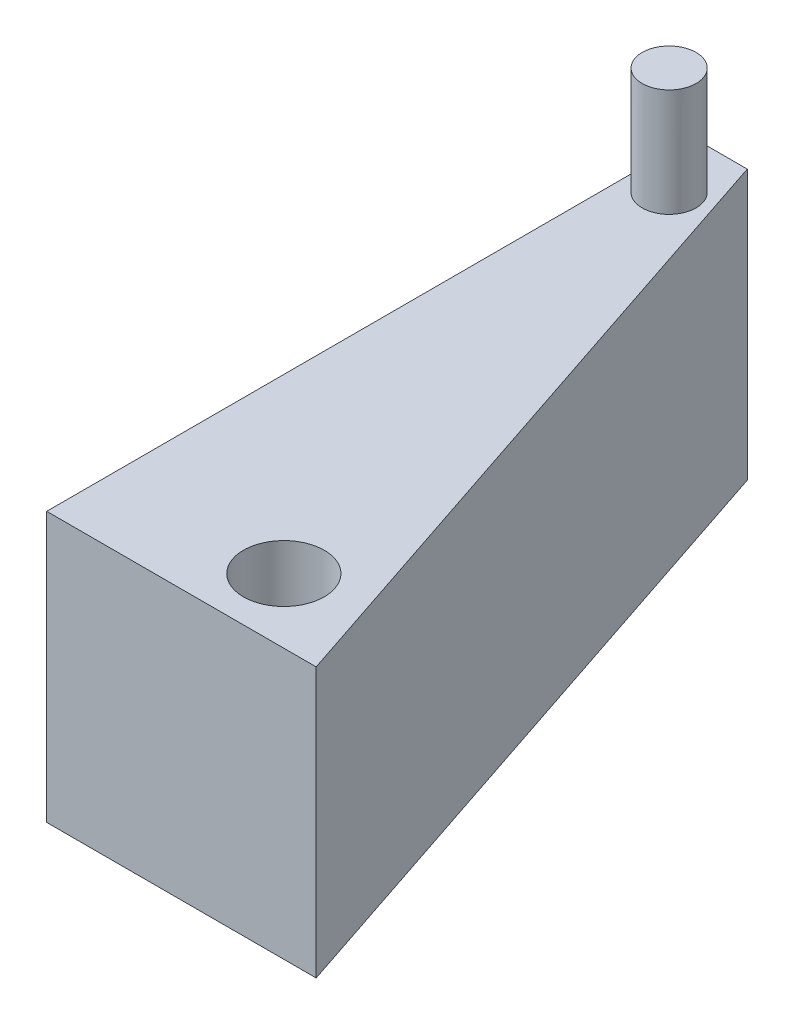
SolidWorks part; units mm, degrees
ref_plane "Front Plane" through (0, 0, 0) normal (0, 0, 1) x (1, 0, 0)
ref_plane "Top Plane" through (0, 0, 0) normal (0, 1, 0) x (1, 0, 0)
ref_plane "Right Plane" through (0, 0, 0) normal (1, 0, 0) x (0, 0, -1)
sketch "Sketch1" plane through (0, 0, 0) normal (0, 1, 0) x (1, 0, 0)
  line L0 (0, 0) -> (0, 76.2)
  line L2 (31.75, 0) -> (0, 0)
  line L3 (0, 76.2) -> (6.35, 76.2)
  line L4 (6.35, 76.2) -> (31.75, 0)
  dimension "D1" = 76.2
  dimension "D2" = 31.75
  dimension "D3" = 6.35
extrude "Boss-Extrude1" add sketch "Sketch1" along normal blind 31.75
sketch "Sketch2" plane through (0, 31.75, 0) normal (0, 1, 0) x (1, 0, 0)
  line L0 (0, 0) -> (0, 7.62) construction
  line L1 (0, 76.2) -> (0, 0) construction
  line L2 (0, 7.62) -> (20.32, 7.62) construction
  circle A0 centre (20.32, 7.62) radius 4.7625
  dimension "D3" = 9.525
  dimension "D1" = 7.62
  dimension "D2" = 20.32
extrude "Cut-Extrude2" cut sketch "Sketch2" against normal through all contours A0
sketch "Sketch3" plane through (0, 31.75, 0) normal (0, 1, 0) x (1, 0, 0)
  line L0 (0, 76.2) -> (0, 69.215) construction
  line L1 (0, 76.2) -> (0, 0) construction
  line L2 (0, 69.215) -> (4.1275, 69.215) construction
  circle A0 centre (4.1275, 69.215) radius 3.175
  dimension "D3" = 6.35
  dimension "D1" = 6.985
  dimension "D2" = 4.1275
extrude "Boss-Extrude2" add sketch "Sketch3" along normal blind 12.7
